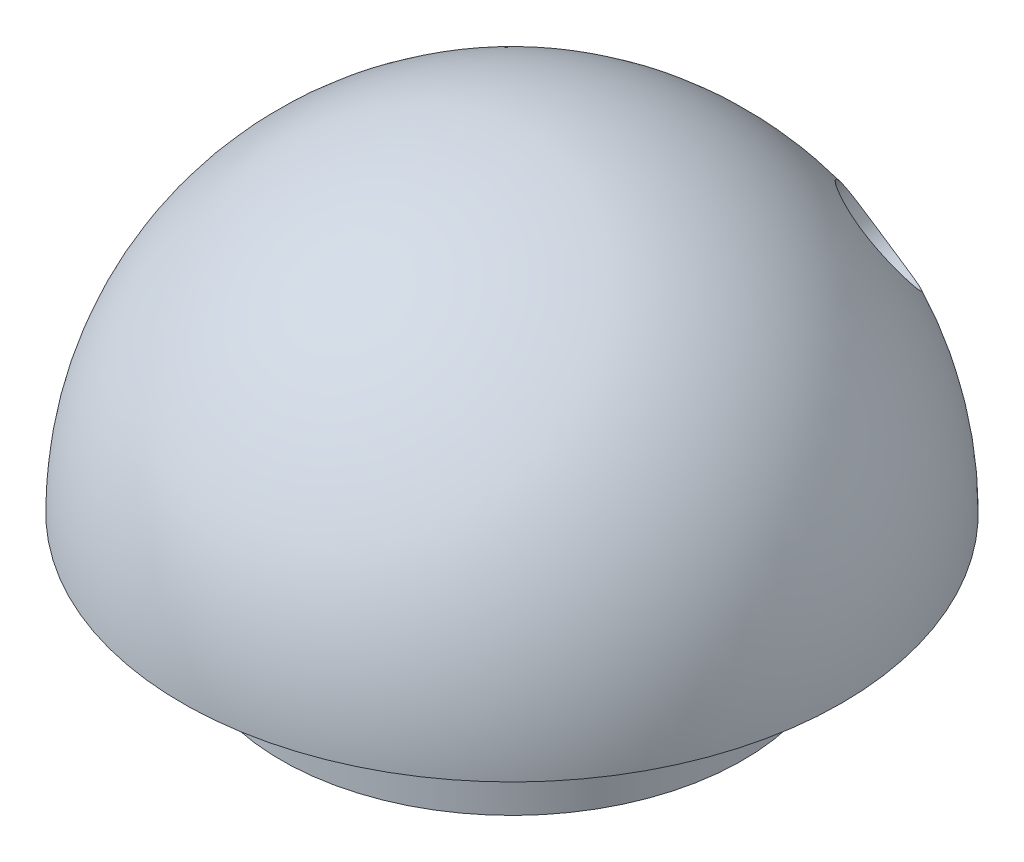
SolidWorks part; units mm, degrees
ref_plane "Front Plane" through (0, 0, 0) normal (0, 0, 1) x (1, 0, 0)
ref_plane "Top Plane" through (0, 0, 0) normal (0, 1, 0) x (1, 0, 0)
ref_plane "Right Plane" through (0, 0, 0) normal (1, 0, 0) x (0, 0, -1)
sketch "Sketch1" plane through (0, 0, 0) normal (0, 0, 1) x (1, 0, 0)
  line L0 (0, 0) -> (0, 86.9355) construction
  line L1 (0, 0) -> (70.1613, 0) construction
  line L2 (17.5, 0) -> (17.5, 7.5)
  line L3 (17.5, 7.5) -> (25, 7.5)
  line L4 (0, 32.5) -> (0, 30)
  line L5 (22.3607, 10) -> (15, 10)
  line L6 (15, 10) -> (15, 0)
  line L7 (15, 0) -> (17.5, 0)
  arc A0 (25, 7.5) -> (0, 32.5) centre (0, 7.5) ccw
  arc A1 (0, 30) -> (22.3607, 10) centre (0, 7.5) cw
  point P12 (0, 0)
  dimension "D6" = 22.5
  dimension "D7" = 25
  dimension "D1" = 15
  dimension "D2" = 2.5
  dimension "D3" = 7.5
  dimension "D4" = 7.5
  dimension "D5" = 10
revolve "Revolve1" add sketch "Sketch1" angle 360 about L0
sketch "Sketch2" plane through (0, 0, 0) normal (0, 0, 1) x (1, 0, 0)
  line L0 (-8.7589, 20.589) -> (8.7589, 20.589) construction
  circle A0 centre (8.7589, 20.589) radius 3.75
  circle A1 centre (-8.7589, 20.589) radius 3.75
  point P4 (0, 20.589)
  dimension "D1" = 7.5
  dimension "D2" = 7.5
extrude "Cut-Extrude1" cut sketch "Sketch2" against normal blind 500
